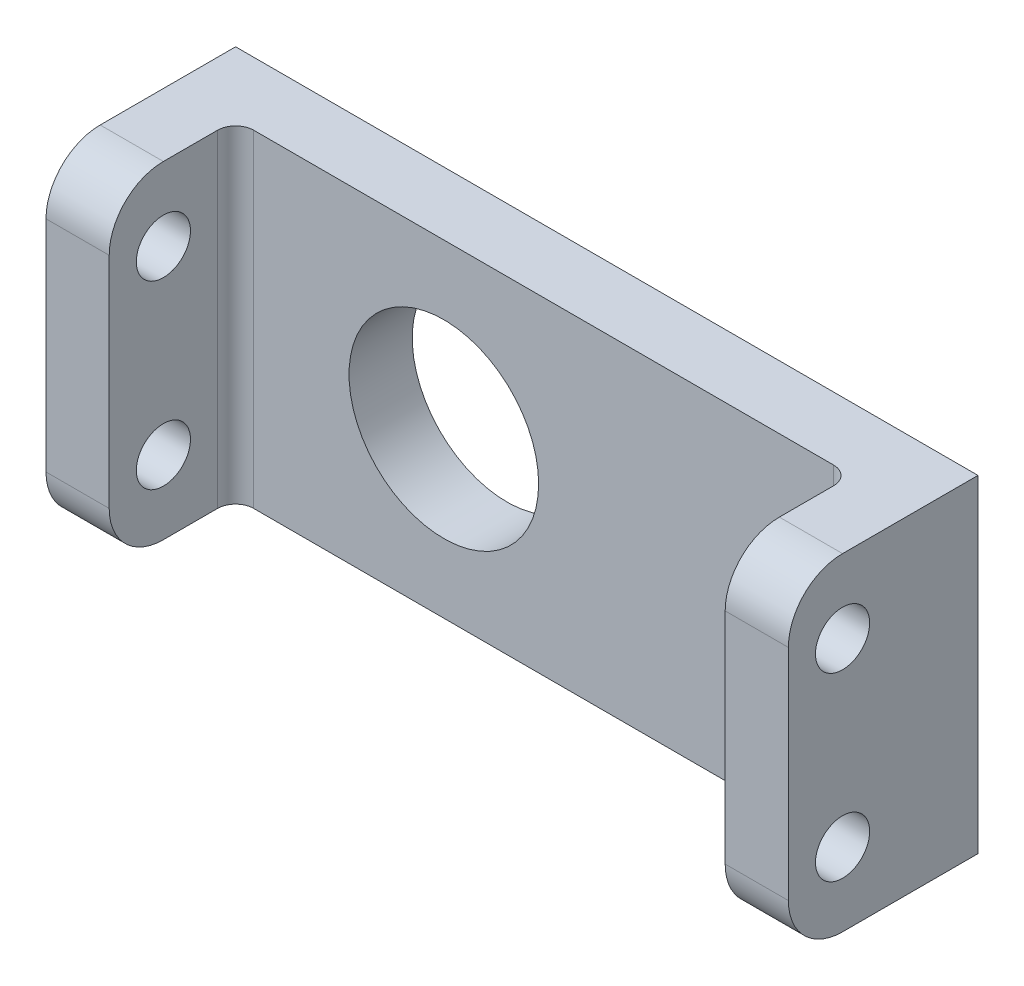
SolidWorks part; units mm, degrees
ref_plane "前视基准面" through (0, 0, 0) normal (0, 0, 1) x (1, 0, 0)
ref_plane "上视基准面" through (0, 0, 0) normal (0, 1, 0) x (1, 0, 0)
ref_plane "右视基准面" through (0, 0, 0) normal (1, 0, 0) x (0, 0, -1)
sketch "草图1" plane through (0, 0, 0) normal (0, 0, 1) x (1, 0, 0)
  line L0 (9.0942, -3.0129) -> (4.3699, -3.0129) construction
  line L1 (8.596, 6.0571) -> (-32.514, 6.0571)
  line L2 (8.596, 6.0571) -> (8.596, -12.0829)
  line L3 (8.596, -12.0829) -> (-32.514, -12.0829)
  line L4 (-32.514, 6.0571) -> (-32.514, -12.0829)
  circle A0 centre (-17.484, -3.0129) radius 5.25
  dimension "D1" = 10.5
  dimension "D2" = 41.11
  dimension "D3" = 18.14
  dimension "D4" = 15.03
extrude "凸台-拉伸1" add sketch "草图1" along normal blind 3.5
sketch "草图3" plane through (0, 0, 3.5) normal (0, 0, 1) x (1, 0, 0)
  line L0 (-32.514, -12.0829) -> (8.596, -12.0829) construction
  line L1 (-32.514, 6.0571) -> (-29.014, 6.0571)
  line L2 (-32.514, 6.0571) -> (-32.514, -12.0829)
  line L3 (-32.514, -12.0829) -> (-29.014, -12.0829)
  line L4 (-29.014, 6.0571) -> (-29.014, -12.0829)
  line L6 (8.596, 6.0571) -> (5.096, 6.0571)
  line L7 (8.596, 6.0571) -> (8.596, -12.0829)
  line L8 (8.596, -12.0829) -> (5.096, -12.0829)
  line L9 (5.096, 6.0571) -> (5.096, -12.0829)
  dimension "D1" = 3.5
  dimension "D2" = 3.5
extrude "凸台-拉伸2" add sketch "草图3" along normal blind 7
sketch "草图4" plane through (8.596, 0, 0) normal (1, 0, 0) x (0, 0, -1)
  line L0 (-7.5, 0.7337) -> (-7.5, 4.6296) construction
  line L1 (-10.5, -12.0829) -> (-10.5, 6.0571) construction
  line L2 (-10.5, -3.0129) -> (-9.1861, -3.0129) construction
  circle A0 centre (-7.5, 1.9871) radius 1.5
  circle A1 centre (-7.5, -8.0129) radius 1.5
  dimension "D1" = 3
  dimension "D2" = 3
  dimension "D3" = 3
  dimension "D4" = 5
  dimension "D5" = 5
extrude "切除-拉伸1" cut sketch "草图4" against normal through all both and the other way through all
fillet "圆角1" radius 1 2 edges at (-29.014, -3.0129, 3.5) (5.096, -3.0129, 3.5)
fillet "圆角2" radius 3 4 edges at (-30.764, 6.0571, 10.5) (-30.764, -12.0829, 10.5) (6.846, 6.0571, 10.5) (6.846, -12.0829, 10.5)
